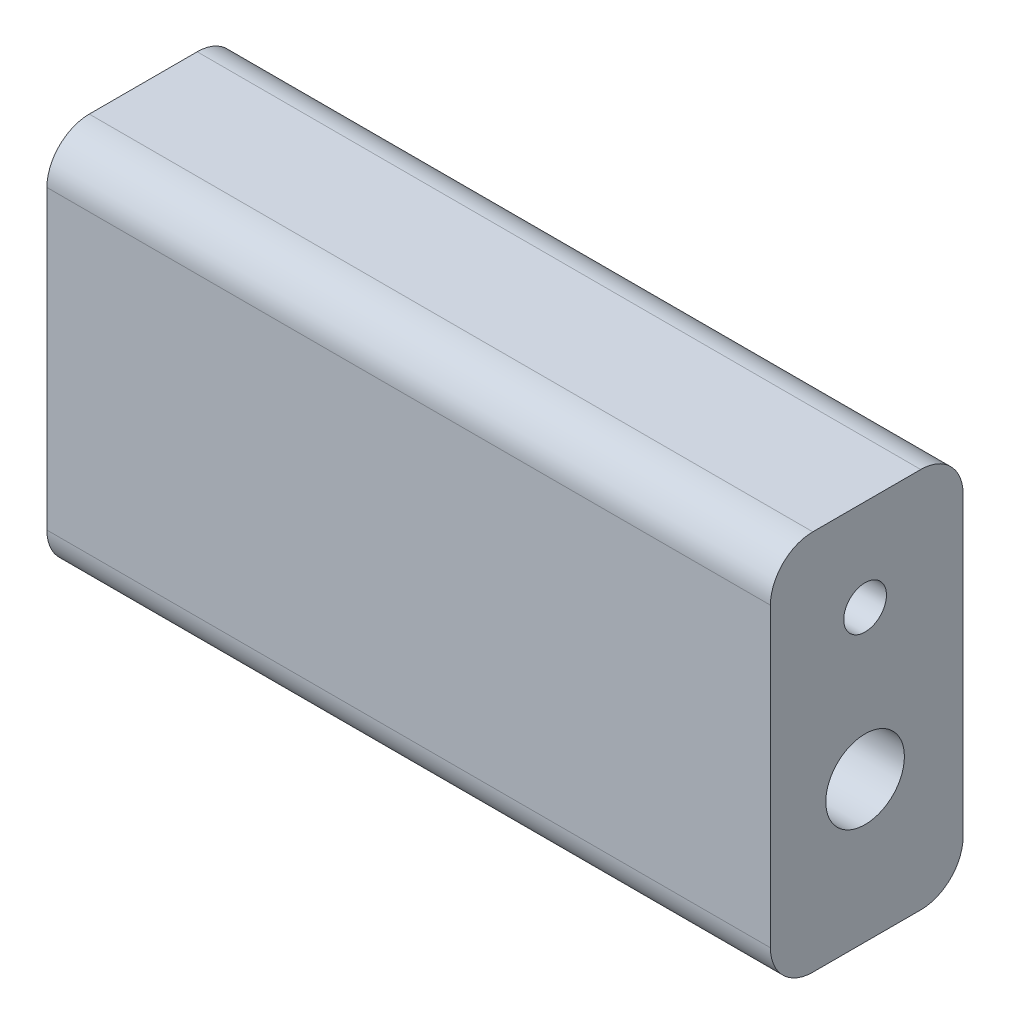
SolidWorks part; units mm, degrees
ref_plane "Front Plane" through (0, 0, 0) normal (0, 0, 1) x (1, 0, 0)
ref_plane "Top Plane" through (0, 0, 0) normal (0, 1, 0) x (1, 0, 0)
ref_plane "Right Plane" through (0, 0, 0) normal (1, 0, 0) x (0, 0, -1)
sketch "Sketch1" plane through (0, 0, 0) normal (0, 0, 1) x (1, 0, 0)
  line L1 (-21.35, 11.255) -> (21.35, 11.255)
  line L2 (-21.35, 11.255) -> (-21.35, -11.255)
  line L3 (-21.35, -11.255) -> (21.35, -11.255)
  line L4 (21.35, 11.255) -> (21.35, -11.255)
  line L5 (-21.35, 11.255) -> (21.35, -11.255) construction
  line L6 (-21.35, -11.255) -> (21.35, 11.255) construction
  point P0 (0, 0)
  dimension "D1" = 22.51
  dimension "D2" = 42.7
extrude "Boss-Extrude1" add sketch "Sketch1" along normal blind 11.37
fillet "Fillet1" radius 2.5 4 edges at (0, -11.255, 11.37) (0, -11.255, 0) (0, 11.255, 0) (0, 11.255, 11.37)
sketch "Sketch2" plane through (21.35, 0, 0) normal (1, 0, 0) x (0, 0, -1)
  circle A0 centre (-5.7841, 5.852) radius 1.26
  circle A1 centre (-5.7841, -2.9317) radius 2.32
  dimension "D1" = 2.52
  dimension "D2" = 4.64
extrude "Cut-Extrude1" cut sketch "Sketch2" against normal blind 12
